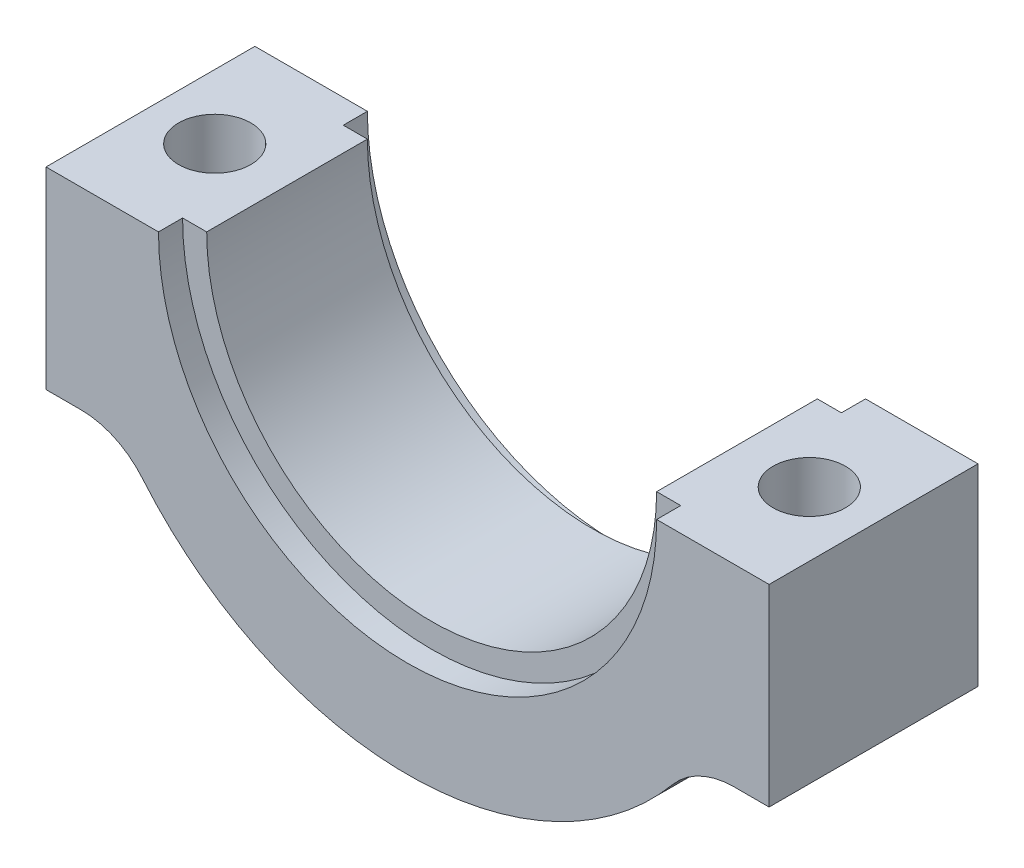
SolidWorks part; units mm, degrees
material "Простая углеродистая сталь"
ref_plane "Front" through (0, 0, 0) normal (0, 0, 1) x (1, 0, 0)
ref_plane "Top" through (0, 0, 0) normal (0, 1, 0) x (1, 0, 0)
ref_plane "Right" through (0, 0, 0) normal (1, 0, 0) x (0, 0, -1)
sketch "Эскиз1" plane through (0, 0, 0) normal (0, 0, 1) x (1, 0, 0)
  line L0 (-122.8769, 68.5524) -> (10.1507, 68.5524) construction
  line L1 (-28, 0) -> (-45, 0)
  line L2 (-45, 0) -> (-45, -24)
  line L3 (0, -61.8265) -> (0, 75.6782) construction
  line L6 (45, 0) -> (45, -24)
  line L7 (28, 0) -> (45, 0)
  line L8 (-45, -24) -> (-40.6571, -24)
  line L9 (45, -24) -> (40.6571, -24)
  arc A7 (-28, 0) -> (28, 0) centre (0, 0) ccw
  arc A8 (-32.986, -27.5849) -> (32.986, -27.5849) centre (0, 0) ccw
  arc A9 (40.6571, -24) -> (32.986, -27.5849) centre (40.6571, -34) ccw
  arc A10 (-32.986, -27.5849) -> (-40.6571, -24) centre (-40.6571, -34) ccw
  point P15 (35.6791, -24)
  point P18 (-35.6791, -24)
  dimension "D1" = 28
  dimension "D2" = 90
  dimension "D4" = 43
  dimension "D5" = 10
  dimension "D3" = 24
extrude "Бобышка-Вытянуть1" add sketch "Эскиз1" along normal mid plane 26
sketch "Эскиз3" plane through (0, 0, -13) normal (0, 0, 1) x (1, 0, 0)
  circle A0 centre (0, 0) radius 31
  dimension "D1" = 31
extrude "Вырез-Вытянуть1" cut sketch "Эскиз3" along normal blind 3
mirror "Зеркальное отражение2" about plane through (0, 0, 0) normal (0, 0, 1) of "Вырез-Вытянуть1"
sketch "Эскиз9" plane through (0, -24, 0) normal (0, -1, 0) x (1, 0, 0)
  line L0 (0, 22.0867) -> (0, -23.52) construction
  circle A0 centre (-37, 0) radius 7
  circle A1 centre (37, 0) radius 7
  dimension "D1" = 74
  dimension "D2" = 14
extrude "Вырез-Вытянуть3" cut sketch "Эскиз9" against normal offset from surface 19 and the other way through all up to face at (33.75, 0, 0)
sketch "Эскиз10" plane through (0, -19, 0) normal (0, -1, 0) x (1, 0, 0)
  circle A0 centre (-37, 0) radius 4.5
  circle A1 centre (37, 0) radius 4.5
  dimension "D1" = 9
extrude "Вырез-Вытянуть4" cut sketch "Эскиз10" against normal through all
